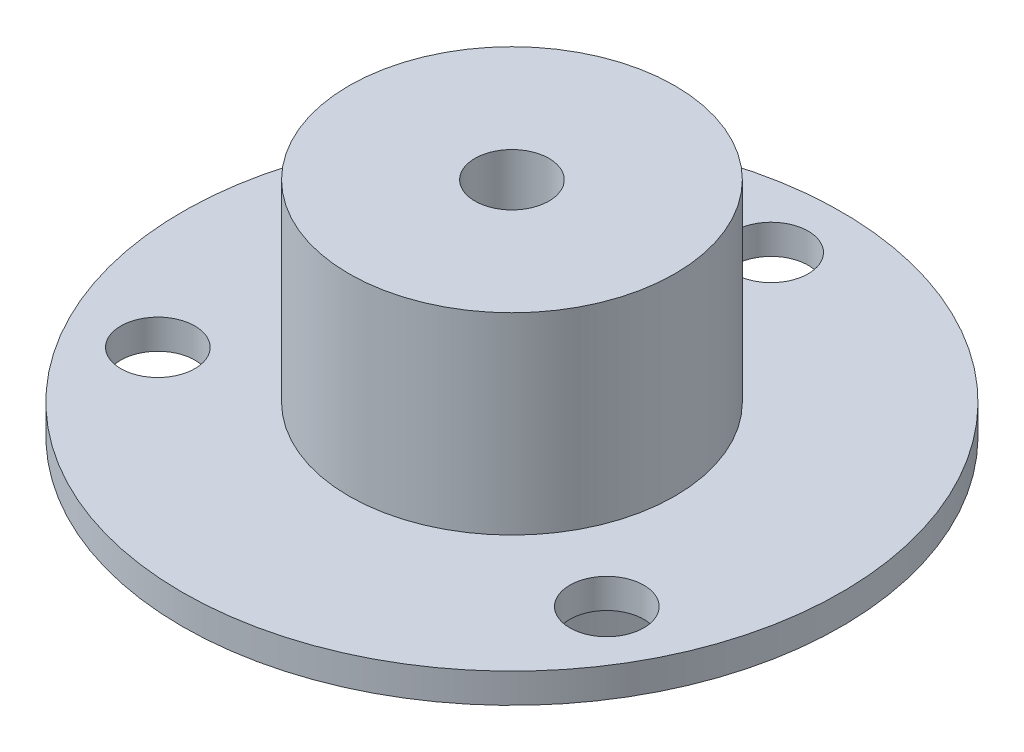
SolidWorks part; units mm, degrees
material "不锈钢 (铁素体)"
ref_plane "前视基准面" through (0, 0, 0) normal (0, 0, 1) x (1, 0, 0)
ref_plane "上视基准面" through (0, 0, 0) normal (0, 1, 0) x (1, 0, 0)
ref_plane "右视基准面" through (0, 0, 0) normal (1, 0, 0) x (0, 0, -1)
other "Configuration Table"
sketch "草图1" plane through (0, 0, 0) normal (0, 1, 0) x (1, 0, 0)
  circle A0 centre (0, 0) radius 22.25
  circle A1 centre (0, 0) radius 17.5 construction
  circle A2 centre (0, 17.5) radius 2.5
  circle A3 centre (-15.1554, -8.75) radius 2.5
  circle A4 centre (15.1554, -8.75) radius 2.5
  dimension "D1" = 44.5
  dimension "D2" = 35
  dimension "D3" = 5
  dimension "D4" = 120
extrude "凸台-拉伸1" add sketch "草图1" along normal blind 2
sketch "草图3" plane through (0, 2, 0) normal (0, 1, 0) x (1, 0, 0)
  circle A0 centre (0, 0) radius 11
  circle A1 centre (0, 0) radius 2.5
  dimension "D1" = 22
  dimension "D2" = 5
extrude "凸台-拉伸3" add sketch "草图3" along normal blind 13
sketch "草图4" plane through (0, 0, 0) normal (0, -1, 0) x (1, 0, 0)
  circle A0 centre (0, 0) radius 11
  dimension "D1" = 22
extrude "凸台-拉伸4" add sketch "草图4" along normal blind 6
sketch "草图6" plane through (0, -6, 0) normal (0, -1, 0) x (1, 0, 0)
  circle A0 centre (0, 0) radius 2.5
extrude "切除-拉伸2" cut sketch "草图6" against normal blind 9
